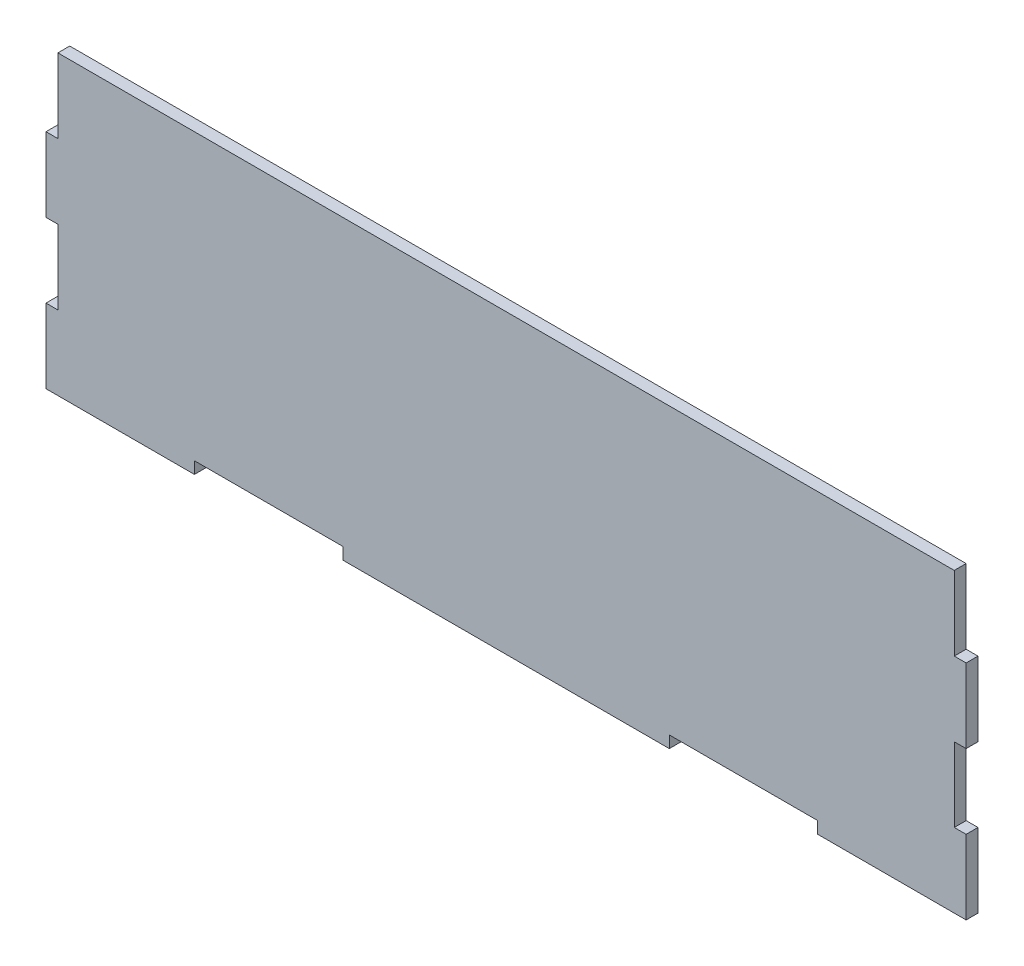
SolidWorks part; units mm, degrees
ref_plane "Alzado" through (0, 0, 0) normal (0, 0, 1) x (1, 0, 0)
ref_plane "Planta" through (0, 0, 0) normal (0, 1, 0) x (1, 0, 0)
ref_plane "Vista lateral" through (0, 0, 0) normal (1, 0, 0) x (0, 0, -1)
sketch "Croquis1" plane through (0, 0, 0) normal (0, 0, 1) x (1, 0, 0)
  line L0 (151, 50) -> (-151, 50)
  line L1 (155, 50) -> (-155, 50) construction
  line L2 (155, 50) -> (155, -50) construction
  line L3 (155, -50) -> (-155, -50) construction
  line L4 (-155, 50) -> (-155, -50) construction
  line L5 (155, 50) -> (-155, -50) construction
  line L6 (155, -50) -> (-155, 50) construction
  line L7 (-151, 50) -> (-151, 25)
  line L8 (-151, 25) -> (-155, 25)
  line L9 (-155, 25) -> (-155, 0)
  line L10 (-155, 0) -> (-151, 0)
  line L11 (-151, 0) -> (-151, -25)
  line L12 (-151, -25) -> (-155, -25)
  line L13 (-155, -25) -> (-155, -50)
  line L14 (-155, -50) -> (-105, -50)
  line L15 (-105, -50) -> (-105, -46)
  line L16 (-105, -46) -> (-55, -46)
  line L17 (-55, -46) -> (-55, -50)
  line L18 (-55, -50) -> (55, -50)
  line L19 (55, -50) -> (55, -46)
  line L20 (55, -46) -> (105, -46)
  line L21 (105, -46) -> (105, -50)
  line L22 (105, -50) -> (155, -50)
  line L23 (155, -50) -> (155, -25)
  line L24 (155, -25) -> (151, -25)
  line L25 (151, -25) -> (151, 0)
  line L26 (151, 0) -> (155, 0)
  line L27 (155, 0) -> (155, 25)
  line L28 (155, 25) -> (151, 25)
  line L29 (151, 25) -> (151, 50)
  point P0 (0, 0)
  dimension "D1" = 310
  dimension "D2" = 100
  dimension "D3" = 25
  dimension "D4" = 50
  dimension "D5" = 4
extrude "Saliente-Extruir1" add sketch "Croquis1" along normal blind 4
equation "\"venesta\"= 4'grosor de la venesta"
equation "\"policarbonato\"= 4'grosor del policarbonato"
equation "\"carton_trupan\"= 3'grosor del carton trupan caso laser"
equation "\"ancho_tot\"= 310'ancho tot sin llantas"
equation "\"largo_tot\"= 400'largo tot sin camera"
equation "\"alto_estimado\"= 300'alto estimado sin lidar"
equation "\"altoparaqpaselabotella\"= 75'alto estimado para que encaje la botella"
equation "\"alturaruedaloca\"= 22"
equation "\"anchoruedaloca\"= 35"
equation "\"anchopiso1motorybaterias\"= 150"
equation "\"dist-pisorampa\"= 5"
equation "\"anchoultimopiso\"= 170"
equation "\"paredtrasera\"= 100"
equation "\"agarradorcanasta\"= 275'recolector"
equation "\"alturapiso1y2\"= 80"
equation "\"alturapiso2y3\"= 80"
equation "\"D1@Croquis1\"=\"ancho_tot\""
equation "\"D2@Croquis1\"=\"paredtrasera\""
equation "\"D5@Croquis1\"=\"policarbonato\""
equation "\"D1@Saliente-Extruir1\"=\"policarbonato\""
